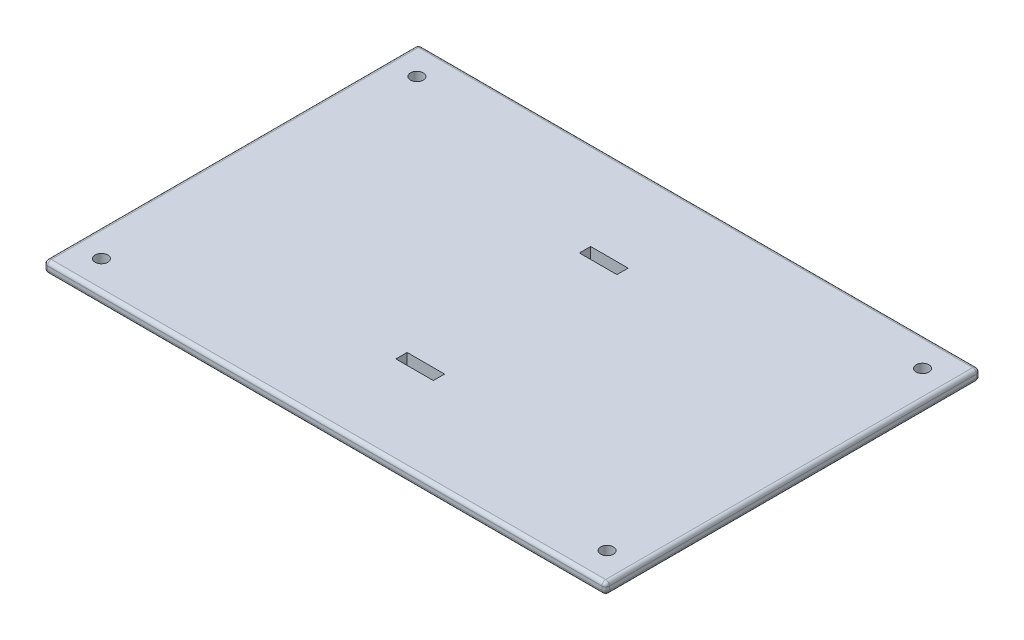
SolidWorks part; units mm, degrees
material "CA"
ref_plane "Plan de face" through (0, 0, 0) normal (0, 0, 1) x (1, 0, 0)
ref_plane "Plan de dessus" through (0, 0, 0) normal (0, 1, 0) x (1, 0, 0)
ref_plane "Plan de droite" through (0, 0, 0) normal (1, 0, 0) x (0, 0, -1)
sketch "Esquisse1" plane through (0, 0, 0) normal (0, 1, 0) x (1, 0, 0)
  line L1 (-75, -50) -> (75, -50)
  line L2 (-75, -50) -> (-75, 50)
  line L3 (-75, 50) -> (75, 50)
  line L4 (75, -50) -> (75, 50)
  line L5 (-75, -50) -> (75, 50) construction
  line L6 (-75, 50) -> (75, -50) construction
  point P0 (0, 0)
  dimension "D1" = 100
  dimension "D2" = 150
extrude "Boss.-Extru.1" add sketch "Esquisse1" along normal blind 3
fillet "Congé1" radius 1 12 edges at (0, 0, -50) (-75, 0, 0) (0, 0, 50) (75, 0, 0) (0, 3, 50) (-75, 3, 0) (0, 3, -50) (75, 3, 0) (75, 1.5, 50) (75, 1.5, -50) (-75, 1.5, -50) (-75, 1.5, 50)
hole_wizard "Dégagement M31" positions "Esquisse3" profile "Esquisse2" hole size "M3" standard "ISO"
sketch "Esquisse3" plane through (0, 3, 0) normal (0, 1, 0) x (-1, 0, 0)
  point P1 (67.5, 42.1132)
  point P4 (-67.5, 42.1132)
  point P7 (-67.5, -42.1132)
  point P10 (67.5, -42.1132)
sketch "Esquisse2" plane through (-67.5, 3, 42.1132) normal (1, 0, 0) x (0, 0, 1)
  line L0 (0, 0) -> (0, 6.0215)
  line L1 (0, 6.0215) -> (1.7, 5)
  line L2 (1.7, 5) -> (1.7, 0)
  line L5 (1.7, 0) -> (0, 0)
  line L10 (0, 6.0215) -> (-1.7, 5) construction
  line L11 (0, -6.35) -> (0, 107.95) construction
  dimension "Diamètre du perçage" = 3.4
  dimension "Profondeur du perçage" = 5
  dimension "Angle de pointe" = 118
sketch "Esquisse4" plane through (0, 3, 0) normal (0, 1, 0) x (1, 0, 0)
  line L1 (-5, 26) -> (5, 26)
  line L2 (-5, 26) -> (-5, 23)
  line L3 (-5, 23) -> (5, 23)
  line L4 (5, 26) -> (5, 23)
  line L5 (-5, 26) -> (5, 23) construction
  line L6 (-5, 23) -> (5, 26) construction
  line L7 (-5, -26) -> (5, -26)
  line L8 (-5, -26) -> (-5, -23)
  line L9 (-5, -23) -> (5, -23)
  line L10 (5, -26) -> (5, -23)
  line L11 (-5, -26) -> (5, -23) construction
  line L12 (-5, -23) -> (5, -26) construction
  point P0 (0, 24.5)
  point P5 (0, -24.5)
  dimension "D1" = 3
  dimension "D2" = 10
  dimension "D3" = 3
  dimension "D4" = 10
  dimension "D5" = 23
  dimension "D6" = 46
extrude "Enlèv. mat.-Extru.1" cut sketch "Esquisse4" against normal blind 3
